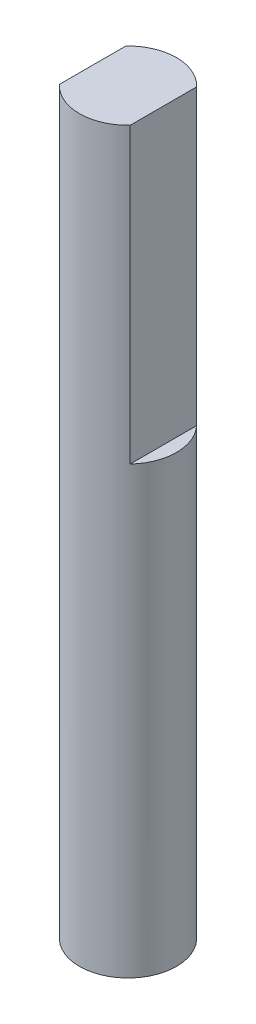
SolidWorks part; units mm, degrees
material "ABS"
ref_plane "Alzado" through (0, 0, 0) normal (0, 0, 1) x (1, 0, 0)
ref_plane "Planta" through (0, 0, 0) normal (0, 1, 0) x (1, 0, 0)
ref_plane "Vista lateral" through (0, 0, 0) normal (1, 0, 0) x (0, 0, -1)
sketch "Croquis2" plane through (0, 0, 0) normal (0, 1, 0) x (1, 0, 0)
  circle A0 centre (0, 0) radius 2.4
  dimension "D1" = 4.8
extrude "Saliente-Extruir1" add sketch "Croquis2" along normal mid plane 36.5
sketch "Croquis3" plane through (0, 18.25, 0) normal (0, 1, 0) x (1, 0, 0)
  line L0 (0, 0) -> (0, 2.4) construction
  line L1 (-1.75, 1.6424) -> (-1.75, -1.6424)
  line L2 (1.75, 1.6424) -> (1.75, -1.6424)
  circle A0 centre (0, 0) radius 2.4 construction
  arc A1 (-1.75, -1.6424) -> (1.75, -1.6424) centre (0, 0) ccw
  arc A2 (1.75, 1.6424) -> (-1.75, 1.6424) centre (0, 0) ccw
  dimension "D1" = 3.5
extrude "Cortar-Extruir-Lámina1" cut sketch "Croquis3" against normal blind 14.5 thin
